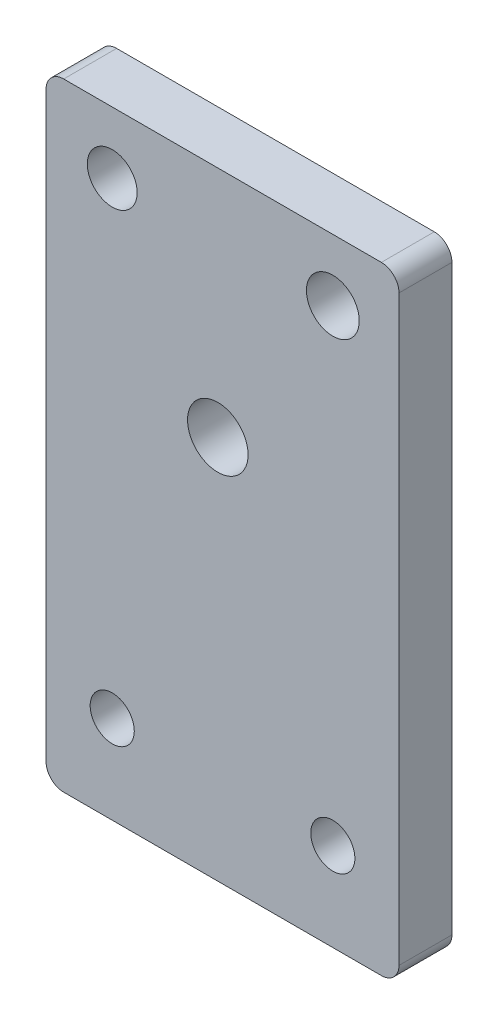
SolidWorks part; units mm, degrees
material "Oak"
ref_plane "Front Plane" through (0, 0, 0) normal (0, 0, 1) x (1, 0, 0)
ref_plane "Top Plane" through (0, 0, 0) normal (0, 1, 0) x (1, 0, 0)
ref_plane "Right Plane" through (0, 0, 0) normal (1, 0, 0) x (0, 0, -1)
sketch "Sketch1" plane through (0, 0, 0) normal (0, 0, 1) x (1, 0, 0)
  line L1 (-7.9379, 18.2609) -> (28.0621, 18.2609)
  line L2 (-9.9379, 16.2609) -> (-9.9379, -49.7391)
  line L3 (-7.9379, -51.7391) -> (28.0621, -51.7391)
  line L4 (30.0621, 16.2609) -> (30.0621, -49.7391)
  arc A0 (-9.9379, -49.7391) -> (-7.9379, -51.7391) centre (-7.9379, -49.7391) ccw
  arc A1 (28.0621, -51.7391) -> (30.0621, -49.7391) centre (28.0621, -49.7391) ccw
  arc A2 (28.0621, 18.2609) -> (30.0621, 16.2609) centre (28.0621, 16.2609) cw
  arc A3 (-7.9379, 18.2609) -> (-9.9379, 16.2609) centre (-7.9379, 16.2609) ccw
  circle A4 centre (-2.4379, 11.2609) radius 2.8241
  circle A5 centre (22.5621, 11.2609) radius 2.9925
  circle A6 centre (-2.4379, -41.7391) radius 2.5
  circle A7 centre (22.5621, -41.7391) radius 2.5
  circle A8 centre (9.5259, -8.1766) radius 3.431
  point P6 (-9.9379, -51.7391)
  point P11 (30.0621, 18.2609)
  point P14 (-9.9379, 18.2609)
  dimension "D3" = 2
  dimension "D7" = 5
  dimension "D8" = 5
  dimension "D1" = 40
  dimension "D2" = 70
  dimension "D4" = 25
  dimension "D5" = 7.5
  dimension "D6" = 7.5
  dimension "D9" = 7.5
  dimension "D10" = 25
  dimension "D11" = 7
  dimension "D12" = 10
extrude "Boss-Extrude1" add sketch "Sketch1" along normal blind 6
